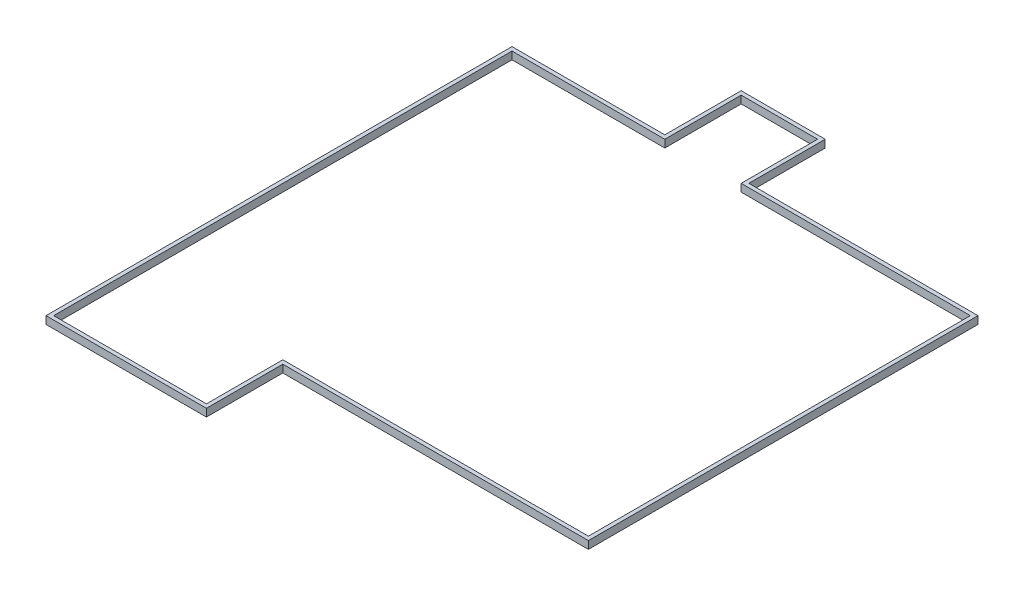
SolidWorks part; units mm, degrees
ref_plane "前视基准面" through (0, 0, 0) normal (0, 0, 1) x (1, 0, 0)
ref_plane "上视基准面" through (0, 0, 0) normal (0, 1, 0) x (1, 0, 0)
ref_plane "右视基准面" through (0, 0, 0) normal (1, 0, 0) x (0, 0, -1)
sketch "草图1" plane through (0, 0, 0) normal (0, 1, 0) x (1, 0, 0)
  line L5 (-2400, 2800) -> (2400, 2800)
  line L6 (-2400, 2800) -> (-2400, -2800)
  line L7 (-2400, -2800) -> (2400, -2800)
  line L8 (2400, 2800) -> (2400, -2800)
  line L9 (0, -2800) -> (0, 2800) construction
  line L10 (-2400, 0) -> (2400, 0) construction
  line L15 (-2400, 2000) -> (2400, 2000) construction
  line L17 (-2400, 1200) -> (2400, 1200) construction
  line L19 (-2400, 400) -> (2400, 400) construction
  line L20 (-2400, -400) -> (2400, -400) construction
  line L21 (-2400, -1200) -> (2400, -1200) construction
  line L22 (-2400, -2000) -> (2400, -2000) construction
  line L23 (-1600, 2800) -> (-1600, -2800) construction
  line L24 (-800, 2800) -> (-800, -2800) construction
  line L25 (0, 2800) -> (0, -2800) construction
  line L26 (800, 2800) -> (800, -2800) construction
  line L27 (1600, 2800) -> (1600, -2800) construction
  point P0 (0, 0)
  dimension "D1" = 4800
  dimension "D2" = 5600
  dimension "D3" = 800
  dimension "D4" = 6
  dimension "D5" = 1600
  dimension "D6" = 800
  dimension "D7" = 5
  dimension "D8" = 1600
sketch "草图3" plane through (0, 0, 0) normal (0, 1, 0) x (1, 0, 0)
  line L0 (-800, 2800) -> (-800, 3600)
  line L1 (-800, 3600) -> (0, 3600)
  line L2 (0, 3600) -> (0, 2800)
  line L3 (0, 2800) -> (-800, 2800)
  dimension "D1" = 800
sketch "草图4" plane through (0, 0, 0) normal (0, 1, 0) x (1, 0, 0)
  line L0 (-800, 2800) -> (-2400, 2800)
  line L4 (-800, 3600) -> (-800, 2800)
  line L5 (0, 3600) -> (-800, 3600)
  line L6 (0, 2800) -> (0, 3600)
  line L7 (-800, 2800) -> (0, 2800)
  line L8 (-800, 3600) -> (-800, 2800)
  line L9 (0, 3600) -> (-800, 3600)
  line L10 (0, 2800) -> (0, 3600)
  line L12 (2400, 2800) -> (-2400, 2800)
  line L13 (2400, -2800) -> (2400, 2800)
  line L14 (-2400, -2800) -> (2400, -2800)
  line L15 (-2400, 2800) -> (-2400, -2800)
  line L16 (2400, 2800) -> (0, 2800)
  line L17 (2400, -1200) -> (2400, 2800)
  line L19 (-2400, 2800) -> (-2400, -2000)
  line L21 (-800, 2800) -> (-800, -2800) construction
  line L22 (-800, -1200) -> (2400, -1200)
  line L23 (-840, 2840) -> (-2440, 2840)
  line L24 (-2440, 2840) -> (-2440, -2040)
  line L27 (-760, -1240) -> (2440, -1240)
  line L28 (2440, -1240) -> (2440, 2840)
  line L29 (2440, 2840) -> (40, 2840)
  line L30 (40, 2840) -> (40, 3640)
  line L31 (40, 3640) -> (-840, 3640)
  line L32 (-840, 3640) -> (-840, 2840)
  line L33 (-2400, -2000) -> (-800, -2000)
  line L35 (-760, -2840) -> (-760, -1240) construction
  line L36 (-2440, -2840) -> (-760, -2840) construction
  line L37 (-2440, 2840) -> (-2440, -2840) construction
  line L38 (-2400, 2800) -> (-2400, -2800) construction
  line L39 (-800, -2800) -> (-800, -1200) construction
  line L40 (-2400, -2800) -> (-800, -2800) construction
  line L41 (-2400, -2000) -> (2400, -2000) construction
  line L42 (-800, -2000) -> (-800, -1200)
  line L43 (-2440, -2040) -> (-760, -2040)
  line L44 (-760, -1240) -> (-760, -2040)
  dimension "D3" = 40
  dimension "D4" = 40
  dimension "D1" = 0
  dimension "D2" = 0
extrude "凸台-拉伸1" add sketch "草图4" along normal blind 80
